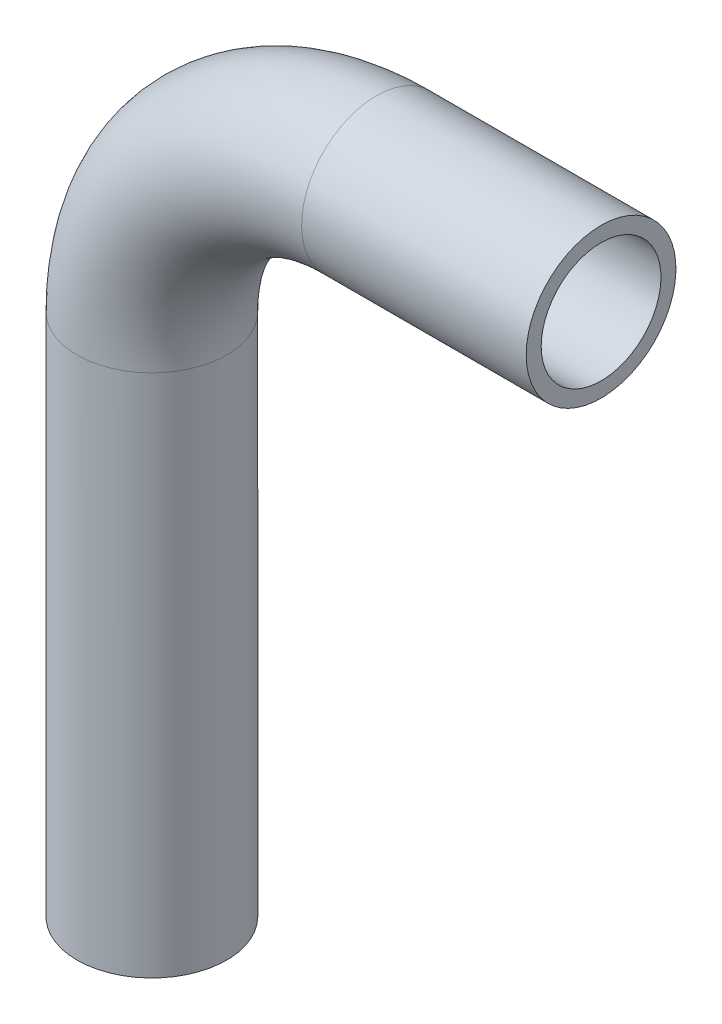
SolidWorks part; units mm, degrees
material "Copper"
ref_plane "Front Plane" through (0, 0, 0) normal (0, 0, 1) x (1, 0, 0)
ref_plane "Top Plane" through (0, 0, 0) normal (0, 1, 0) x (1, 0, 0)
ref_plane "Right Plane" through (0, 0, 0) normal (1, 0, 0) x (0, 0, -1)
sketch "Sketch1" plane through (0, 0, 0) normal (0, 1, 0) x (1, 0, 0)
  circle A0 centre (0, 0) radius 12.7
  circle A1 centre (0, 0) radius 10.16
  dimension "D1" = 25.4
  dimension "D2" = 20.32
sketch "Sketch3" plane through (0, 0, 0) normal (0, 0, 1) x (1, 0, 0)
  line L0 (0, 0) -> (0, 88.9)
  line L1 (38.1, 127) -> (76.2, 127)
  arc A0 (38.1, 127) -> (0, 88.9) centre (38.1, 88.9) ccw
  dimension "D3" = 76.2
  dimension "D1" = 88.9
  dimension "D2" = 38.1
  dimension "D4" = 38.1
sweep "Sweep1" add profiles "Sketch1" path "Sketch3"
